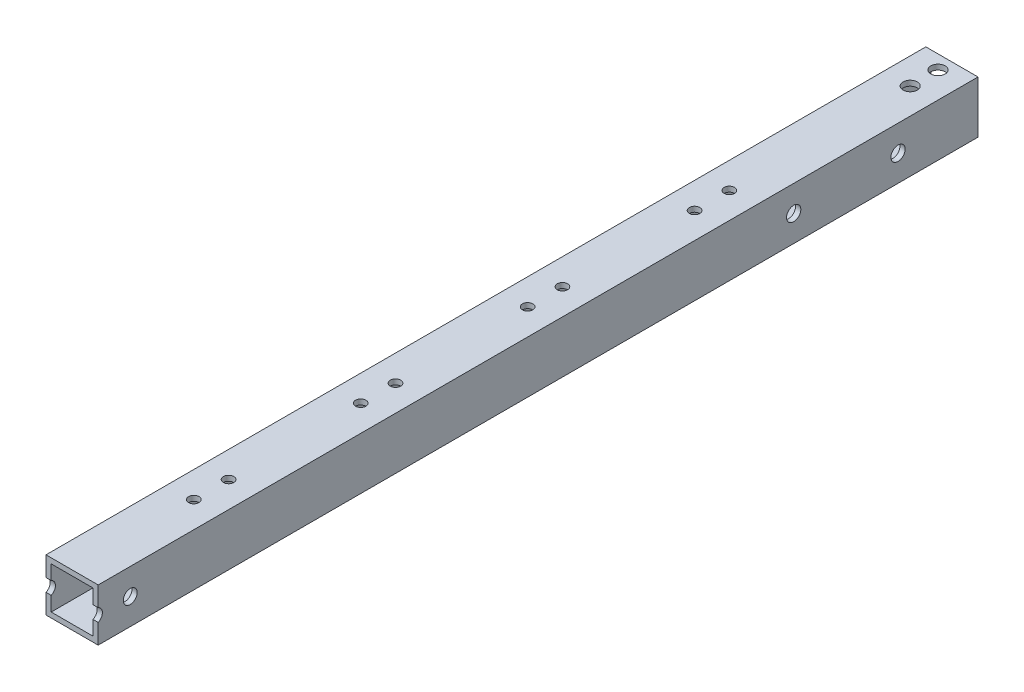
SolidWorks part; units mm, degrees
ref_plane "前视基准面" through (0, 0, 0) normal (0, 0, 1) x (1, 0, 0)
ref_plane "上视基准面" through (0, 0, 0) normal (0, 1, 0) x (1, 0, 0)
ref_plane "右视基准面" through (0, 0, 0) normal (1, 0, 0) x (0, 0, -1)
sketch "草图1" plane through (0, 0, 0) normal (0, 0, 1) x (1, 0, 0)
  line L1 (-6, 6) -> (6, 6)
  line L2 (-6, 6) -> (-6, -6)
  line L3 (-6, -6) -> (6, -6)
  line L4 (6, 6) -> (6, -6)
  line L5 (-6, 6) -> (6, -6) construction
  line L6 (-6, -6) -> (6, 6) construction
  line L7 (-7.5, -7.5) -> (7.5, -7.5)
  line L8 (-7.5, -7.5) -> (-7.5, 7.5)
  line L9 (-7.5, 7.5) -> (7.5, 7.5)
  line L10 (7.5, -7.5) -> (7.5, 7.5)
  line L11 (-7.5, -7.5) -> (7.5, 7.5) construction
  line L12 (-7.5, 7.5) -> (7.5, -7.5) construction
  point P0 (0, 0)
  point P5 (0, 0)
  dimension "D1" = 15
  dimension "D2" = 15
  dimension "D3" = 1.5
  dimension "D4" = 1.5
extrude "凸台-拉伸1" add sketch "草图1" along normal blind 375
sketch "草图3" plane through (0, 7.5, 0) normal (0, 1, 0) x (1, 0, 0)
  line L0 (7.5, 0) -> (-7.5, 0) construction
  circle A0 centre (0, -4) radius 2.05
  circle A1 centre (0, -12) radius 2.05
  dimension "D1" = 4.1
  dimension "D2" = 4
  dimension "D3" = 8
extrude "切除-拉伸2" cut sketch "草图3" against normal blind 21
sketch "草图4" plane through (7.5, 0, 0) normal (1, 0, 0) x (0, 0, -1)
  line L0 (0, -7.5) -> (0, 7.5) construction
  circle A0 centre (-23, 0) radius 2.05
  circle A1 centre (-53, 0) radius 2.05
  dimension "D1" = 30
  dimension "D3" = 4.1
  dimension "D2" = 23
extrude "切除-拉伸3" cut sketch "草图4" against normal blind 25
sketch "草图6" plane through (0, 7.5, 0) normal (0, 1, 0) x (1, 0, 0)
  line L0 (7.5, -375) -> (-7.5, -375) construction
  line L1 (7.5, -375) -> (7.5, 0) construction
  circle A0 centre (0, -335) radius 2
  circle A1 centre (0, -350) radius 2
  dimension "D1" = 25
  dimension "D3" = 4
  dimension "D2" = 40
  dimension "D4" = 7.5
extrude "切除-拉伸5" cut sketch "草图6" against normal blind 75
sketch "草图7" plane through (7.5, 0, 0) normal (1, 0, 0) x (0, 0, -1)
  line L1 (-253.7868, 0) -> (-243.7868, 0) construction
  circle A0 centre (-253.7868, 0) radius 2
  circle A1 centre (-243.7868, 0) radius 2
  dimension "D1" = 4
  dimension "D2" = 4
  dimension "D3" = 10
extrude "切除-拉伸6" cut sketch "草图7" against normal through all
sketch "草图8" plane through (7.5, 0, 0) normal (1, 0, 0) x (0, 0, -1)
  line L0 (-375, -7.5) -> (0, -7.5) construction
  line L1 (-375, 7.5) -> (-253, 7.5)
  line L2 (-375, 7.5) -> (-375, -7.5)
  line L3 (-375, -7.5) -> (-253, -7.5)
  line L4 (-253, 7.5) -> (-253, -7.5)
  dimension "D1" = 122
extrude "切除-拉伸7" cut sketch "草图8" against normal through all
sketch "草图9" plane through (0, 7.5, 0) normal (0, 1, 0) x (1, 0, 0)
  line L0 (0, -253) -> (0, 0) construction
  line L1 (-7.5, -253) -> (7.5, -253) construction
  circle A0 centre (0, -218) radius 1.5
  circle A1 centre (0, -208) radius 1.5
  circle A2 centre (0, -170) radius 1.5
  circle A3 centre (0, -160) radius 1.5
  circle A4 centre (0, -122) radius 1.5
  circle A5 centre (0, -112) radius 1.5
  circle A6 centre (0, -74) radius 1.5
  circle A7 centre (0, -64) radius 1.5
  dimension "D1" = 3
  dimension "D2" = 3
  dimension "D3" = 10
  dimension "D4" = 35
  dimension "D6" = 48
  dimension "D5" = 4
extrude "切除-拉伸8" cut sketch "草图9" against normal through all
